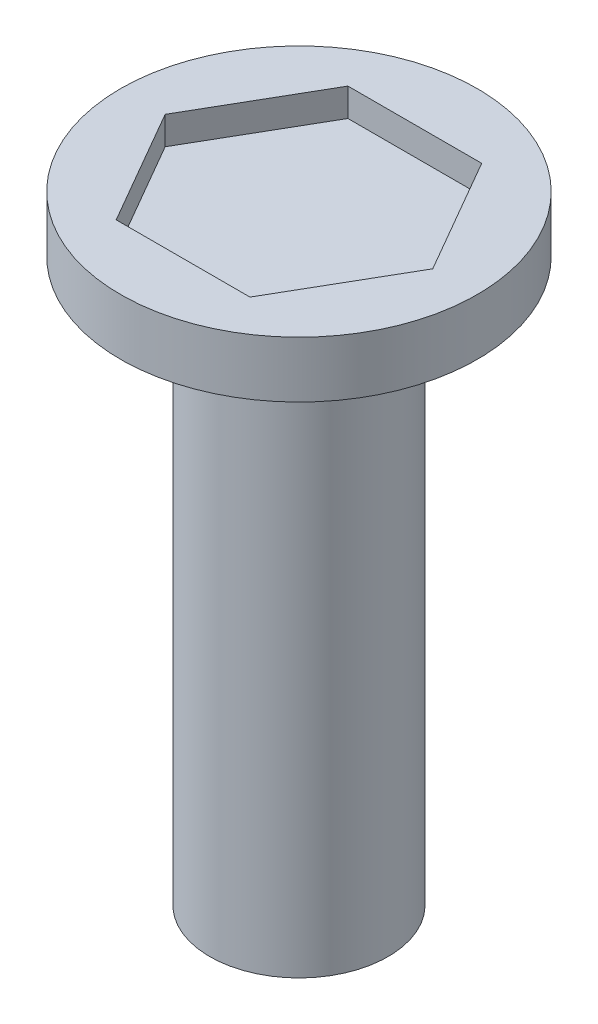
SolidWorks part; units mm, degrees
material "1060 Alloy"
ref_plane "Front Plane" through (0, 0, 0) normal (0, 0, 1) x (1, 0, 0)
ref_plane "Top Plane" through (0, 0, 0) normal (0, 1, 0) x (1, 0, 0)
ref_plane "Right Plane" through (0, 0, 0) normal (1, 0, 0) x (0, 0, -1)
sketch "Sketch1" plane through (0, 0, 0) normal (0, 0, 1) x (1, 0, 0)
  line L0 (0, 0) -> (3.175, 0)
  line L1 (3.175, 0) -> (3.175, -11)
  line L2 (3.175, -11) -> (1.5875, -11)
  line L3 (1.5875, -11) -> (1.5875, -1)
  line L4 (1.5875, -1) -> (0, -1)
  line L5 (0, -1) -> (0, 0)
  dimension "D1" = 1.5875
  dimension "D2" = 10
  dimension "D3" = 1
  dimension "D4" = 3.175
revolve "Revolve1" add sketch "Sketch1" angle 360 about L1
sketch "Sketch2" plane through (0, 0, 0) normal (0, 1, 0) x (1, 0, 0)
  line L1 (5.5562, 0) -> (4.3656, 2.0622)
  line L2 (4.3656, 2.0622) -> (1.9844, 2.0622)
  line L3 (1.9844, 2.0622) -> (0.7937, 0)
  line L4 (0.7937, 0) -> (1.9844, -2.0622)
  line L5 (1.9844, -2.0622) -> (4.3656, -2.0622)
  line L6 (4.3656, -2.0622) -> (5.5562, 0)
  circle A0 centre (3.175, 0) radius 3.175 construction
  circle A1 centre (3.175, 0) radius 2.3813 construction
  point P0 (3.175, 3.175)
  point P1 (0, 0)
extrude "Cut-Extrude1" cut sketch "Sketch2" against normal blind 0.5
